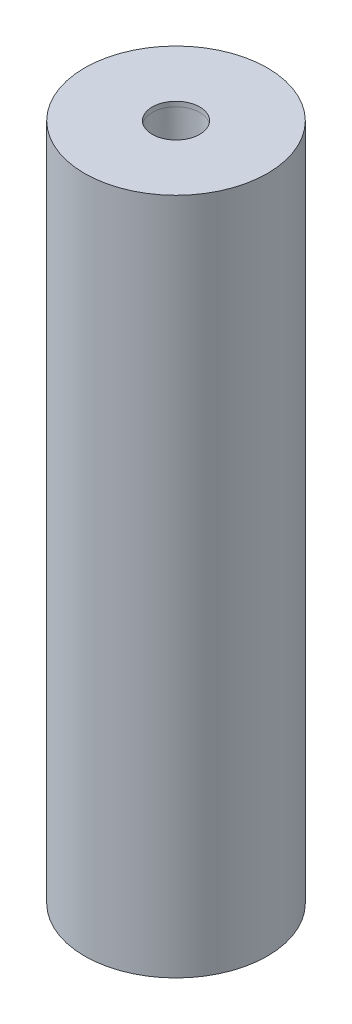
SolidWorks part; units mm, degrees
ref_plane "Front Plane" through (0, 0, 0) normal (0, 0, 1) x (1, 0, 0)
ref_plane "Top Plane" through (0, 0, 0) normal (0, 1, 0) x (1, 0, 0)
ref_plane "Right Plane" through (0, 0, 0) normal (1, 0, 0) x (0, 0, -1)
sketch "Sketch1" plane through (0, 0, 0) normal (0, 0, 1) x (1, 0, 0)
  line L0 (0, 0) -> (0, 140) construction
  line L1 (-2.5175, 1) -> (-4.9437, 140)
  line L2 (-123.5875, 0) -> (0, 0) construction
  line L3 (0, 140) -> (-123.5875, 140) construction
  line L4 (-5.9439, 140) -> (-3.5002, 0)
  line L5 (-3.5002, 0) -> (-2.5, 0)
  line L8 (-5.7693, 0) -> (-8.213, 140)
  line L9 (-6.7695, 0) -> (-5.7693, 0)
  line L10 (-9.2132, 140) -> (-6.7695, 0)
  line L12 (-9.0387, 0) -> (-11.4824, 140)
  line L13 (-10.0388, 0) -> (-9.0387, 0)
  line L14 (-12.4825, 140) -> (-10.0388, 0)
  line L16 (-12.308, 0) -> (-14.7517, 140)
  line L17 (-13.3082, 0) -> (-12.308, 0)
  line L18 (-15.7519, 140) -> (-13.3082, 0)
  line L20 (-15.5773, 0) -> (-18.0211, 140)
  line L33 (-19.0211, 140) -> (-19.0211, 141)
  line L34 (-19.0211, 141) -> (-4.9437, 141)
  line L35 (-4.9437, 140) -> (-4.9437, 141)
  line L36 (-19.0211, 0) -> (-15.5773, 0)
  line L39 (-18.0211, 140) -> (-15.7519, 140)
  line L41 (-14.7517, 140) -> (-12.4825, 140)
  line L43 (-11.4824, 140) -> (-9.2132, 140)
  line L45 (-8.213, 140) -> (-5.9439, 140)
  line L46 (-2.5, 0) -> (0, 0)
  line L47 (0, 0) -> (0, 1)
  line L48 (0, 1) -> (-2.5175, 1)
  line L49 (-19.0211, 140) -> (-19.0211, 0)
  line L52 (-25.5599, 140) -> (-23.1162, 0) [skipped]
  line L53 (-22.116, 0) -> (-24.5597, 140) [skipped]
  line L54 (-23.1162, 0) -> (-22.116, 0) [skipped]
  line L55 (-19.8468, 0) -> (-18.8467, 0) [skipped]
  line L56 (-20.6716, 47.2479) -> (-19.8468, 0) [skipped]
  line L57 (-18.8467, 0) -> (-20.6716, 104.5465) [skipped]
  line L58 (-19.0212, 140) -> (-16.5775, 0) [skipped]
  line L59 (-16.5775, 0) -> (-15.5773, 0) [skipped]
  dimension "D1" = 89
  dimension "D2" = 140
  dimension "D3" = 2.5
  dimension "D4" = 1
  dimension "D6" = 1
  dimension "D7" = 1
  dimension "D8" = 1
  dimension "D9" = 2.2692
  dimension "D10" = 1
  dimension "D5" = 7
revolve "Revolve2" add sketch "Sketch1" angle 360 about L0
